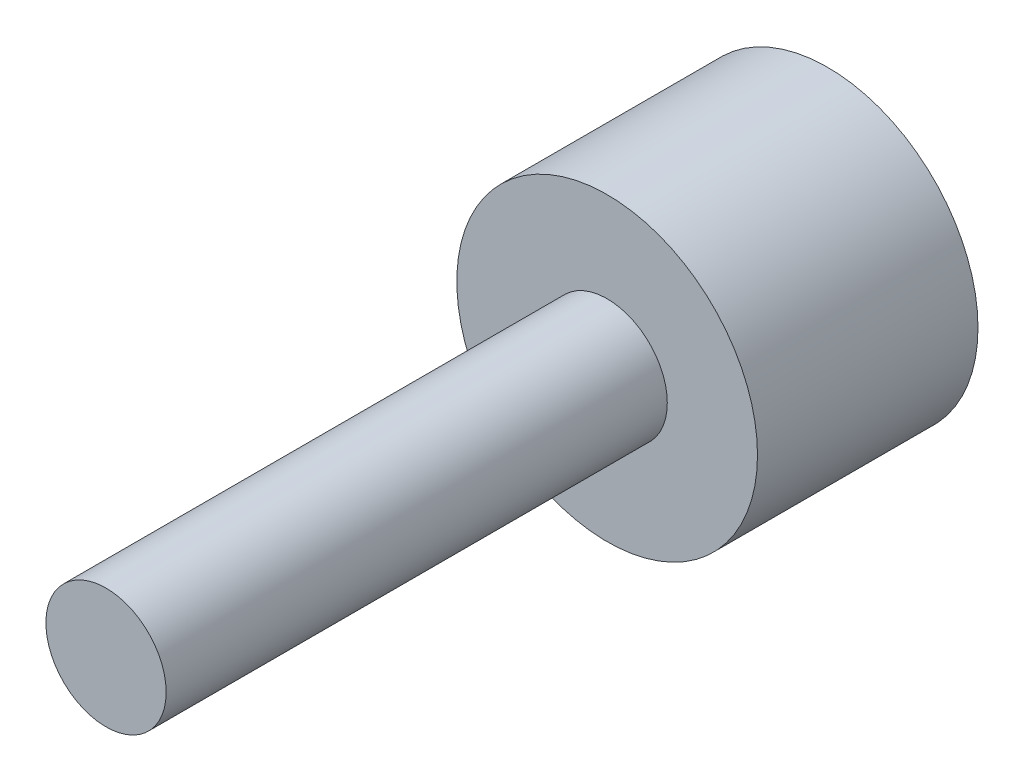
SolidWorks part; units mm, degrees
ref_plane "前视基准面" through (0, 0, 0) normal (0, 0, 1) x (1, 0, 0)
ref_plane "上视基准面" through (0, 0, 0) normal (0, 1, 0) x (1, 0, 0)
ref_plane "右视基准面" through (0, 0, 0) normal (1, 0, 0) x (0, 0, -1)
sketch "草图1" plane through (0, 0, 0) normal (0, 0, 1) x (1, 0, 0)
  circle A0 centre (0, 0) radius 7.5
  dimension "D1" = 15
extrude "凸台-拉伸1" add sketch "草图1" along normal mid plane 11
sketch "草图2" plane through (0, 0, 5.5) normal (0, 0, 1) x (1, 0, 0)
  circle A0 centre (0, 0) radius 3
  dimension "D1" = 6
extrude "凸台-拉伸2" add sketch "草图2" along normal blind 25
